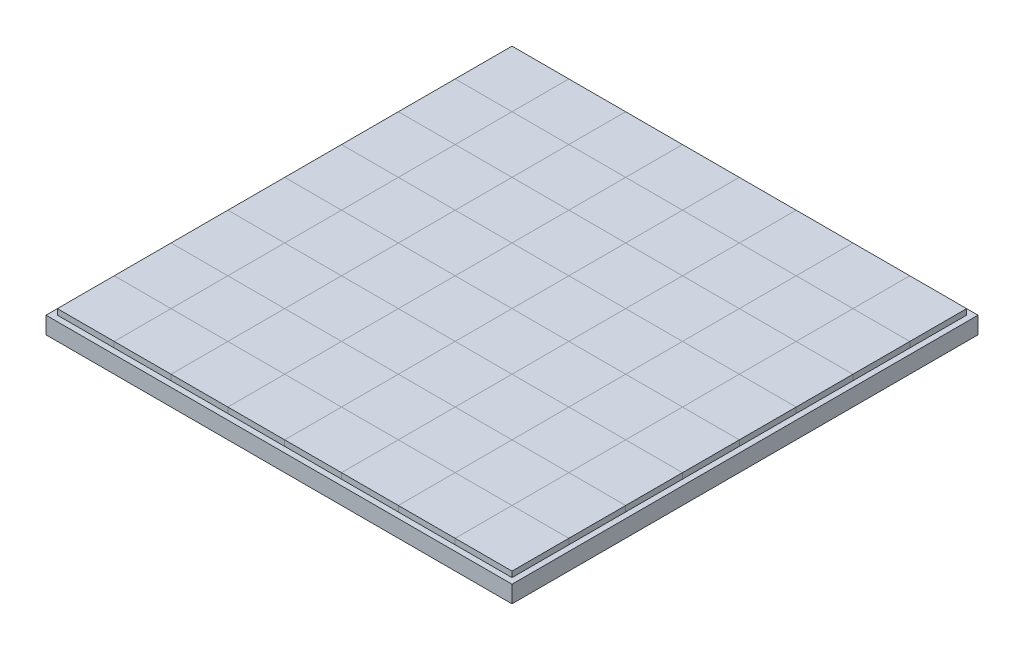
SolidWorks part; units mm, degrees
ref_plane "Front Plane" through (0, 0, 0) normal (0, 0, 1) x (1, 0, 0)
ref_plane "Top Plane" through (0, 0, 0) normal (0, 1, 0) x (1, 0, 0)
ref_plane "Right Plane" through (0, 0, 0) normal (1, 0, 0) x (0, 0, -1)
sketch "Sketch1" plane through (0, 0, 0) normal (0, 1, 0) x (1, 0, 0)
  line L1 (210, 200) -> (-200, 200)
  line L2 (210, 200) -> (210, -210)
  line L3 (210, -210) -> (-200, -210)
  line L4 (-200, 200) -> (-200, -210)
  dimension "D10" = 410
extrude "Boss-Extrude3" add sketch "Sketch1" along normal blind 15
sketch "Sketch2" plane through (0, 15, 0) normal (0, 1, 0) x (1, 0, 0)
  line L0 (-200, 200) -> (-200, -210) construction
  line L5 (-145, 195) -> (-195, 195)
  line L6 (-145, 195) -> (-145, 145)
  line L7 (-145, 145) -> (-195, 145)
  line L8 (-195, 195) -> (-195, 145)
  line L9 (-145, 195) -> (-195, 145) construction
  line L10 (-145, 145) -> (-195, 195) construction
  line L12 (210, 200) -> (-200, 200) construction
  point P0 (-170, 170)
  dimension "D1" = 50
  dimension "D2" = 5
  dimension "D3" = 5
extrude "Boss-Extrude4" add sketch "Sketch2" along normal blind 5
pattern_linear "LPattern2" count 4 spacing 100 along (1, 0, 0) count 4 spacing 100 along (0, 0, 1) of "Boss-Extrude4"
sketch "Sketch3" plane through (0, 15, 0) normal (0, 1, 0) x (1, 0, 0)
  line L1 (-145, 195) -> (-95, 195)
  line L2 (-145, 195) -> (-145, 145)
  line L3 (-145, 145) -> (-95, 145)
  line L4 (-95, 195) -> (-95, 145)
extrude "Boss-Extrude6" add sketch "Sketch3" along normal blind 5 separate body
pattern_linear "LPattern3" count 4 spacing 100 along (1, 0, 0) count 4 spacing 100 along (0, 0, 1) of "Boss-Extrude6"
sketch "Sketch5" plane through (0, 15, 0) normal (0, 1, 0) x (1, 0, 0)
  line L1 (-145, 145) -> (-195, 145)
  line L2 (-145, 145) -> (-145, 95)
  line L3 (-145, 95) -> (-195, 95)
  line L4 (-195, 145) -> (-195, 95)
extrude "Boss-Extrude7" add sketch "Sketch5" along normal blind 5 separate body
pattern_linear "LPattern4" count 4 spacing 100 along (1, 0, 0) count 4 spacing 100 along (0, 0, 1) of "Boss-Extrude7"
sketch "Sketch6" plane through (0, 15, 0) normal (0, 1, 0) x (1, 0, 0)
  line L1 (-145, 145) -> (-95, 145)
  line L2 (-145, 145) -> (-145, 95)
  line L3 (-145, 95) -> (-95, 95)
  line L4 (-95, 145) -> (-95, 95)
extrude "Boss-Extrude8" add sketch "Sketch6" along normal blind 5 separate body
pattern_linear "LPattern5" count 4 spacing 100 along (1, 0, 0) count 4 spacing 100 along (0, 0, 1) of "Boss-Extrude8"
